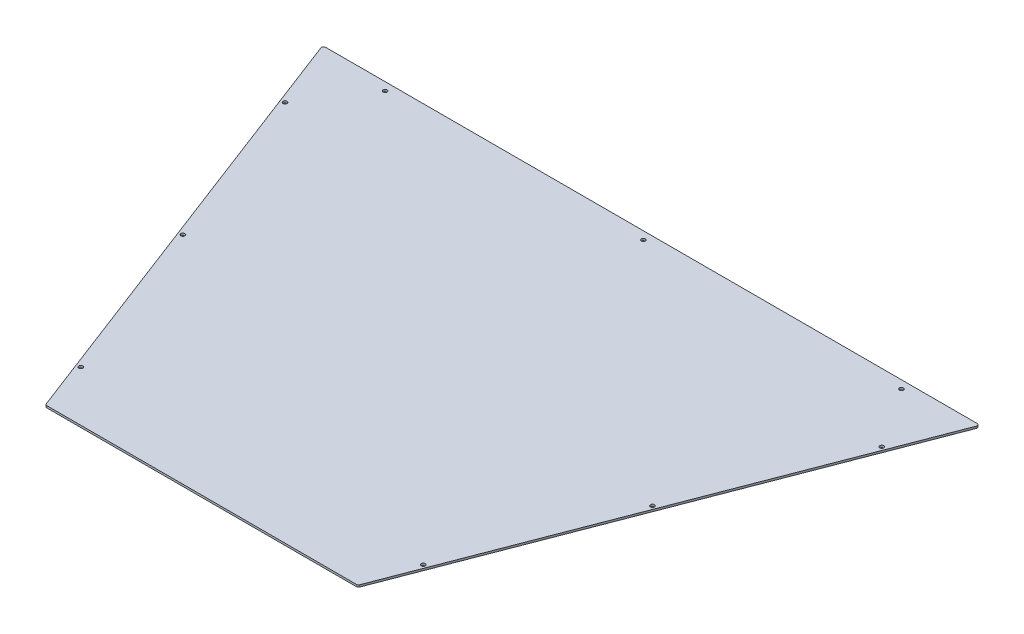
SolidWorks part; units mm, degrees
material "PE High Density"
ref_plane "Front Plane" through (0, 0, 0) normal (0, 0, 1) x (1, 0, 0)
ref_plane "Top Plane" through (0, 0, 0) normal (0, 1, 0) x (1, 0, 0)
ref_plane "Right Plane" through (0, 0, 0) normal (1, 0, 0) x (0, 0, -1)
sketch "Sketch1" plane through (0, 0, 0) normal (0, 1, 0) x (1, 0, 0)
  line L0 (-245.912, 0) -> (245.912, 0)
  line L1 (245.912, 0) -> (517.525, 708.025)
  line L2 (517.525, 708.025) -> (-517.525, 708.025)
  line L3 (-517.525, 708.025) -> (-245.912, 0)
  dimension "D1" = 1035.05
  dimension "D2" = 69.012
  dimension "D3" = 708.025
extrude "Boss-Extrude1" add sketch "Sketch1" along normal blind 3.175
fillet "Fillet1" radius 3.175 4 edges at (517.525, 1.5875, -708.025) (-517.525, 1.5875, -708.025) (-245.912, 1.5875, 0) (245.912, 1.5875, 0)
sketch "Sketch2" plane through (0, 3.175, 0) normal (0, 1, 0) x (1, 0, 0)
  line L0 (512.9064, 708.025) -> (-512.9064, 708.025) construction
  line L1 (-469.6817, 601.0389) -> (-269.5364, 79.3117) construction
  line L2 (469.6817, 601.0389) -> (269.5364, 79.3117) construction
  line L3 (-515.8708, 703.7128) -> (-246.6937, 2.0378) construction
  line L4 (246.6937, 2.0378) -> (515.8708, 703.7128) construction
  point P0 (0, 695.325)
  point P1 (-406.4, 695.325)
  point P2 (406.4, 695.325)
  point P5 (0, 708.025)
  point P6 (-469.6817, 601.0389)
  point P7 (-369.609, 340.1753)
  point P8 (-269.5364, 79.3117)
  point P9 (269.5364, 79.3117)
  point P10 (369.609, 340.1753)
  point P11 (469.6817, 601.0389)
  point P23 (-381.2822, 352.8753)
  dimension "D1" = 12.7
  dimension "D2" = 406.4
  dimension "D3" = 406.4
  dimension "D4" = 6.35
  dimension "D5" = 6.35
  dimension "D6" = 558.8
  dimension "D7" = 12.7
hole_wizard "1/4 (0.25) Diameter Hole1" positions "Sketch3" profile "Sketch4" hole size "1/4" standard "ANSI Inch" end condition through all
sketch "Sketch3" plane through (0, 3.175, 0) normal (0, 1, 0) x (1, 0, 0)
  line L0 (469.6817, 601.0389) -> (269.5364, 79.3117) construction
  point P0 (-406.4, 695.325)
  point P3 (0, 695.325)
  point P6 (406.4, 695.325)
  point P9 (-469.6817, 601.0389)
  point P12 (-369.609, 340.1753)
  point P15 (-269.5364, 79.3117)
  point P18 (269.5364, 79.3117)
  point P23 (369.609, 340.1753)
  point P27 (469.6817, 601.0389)
sketch "Sketch4" plane through (-406.4, 3.175, -695.325) normal (1, 0, 0) x (0, 0, 1)
  line L0 (0, 0) -> (0, 3.175)
  line L1 (0, 3.175) -> (3.175, 3.175)
  line L2 (3.175, 3.175) -> (3.175, 0)
  line L5 (3.175, 0) -> (0, 0)
  line L11 (0, -6.35) -> (0, 107.95) construction
  dimension "Thru Hole Dia." = 6.35
  dimension "Thru Hole Depth" = 3.175
equation "\"D3@Sketch2\"=\"D2@Sketch2\""
